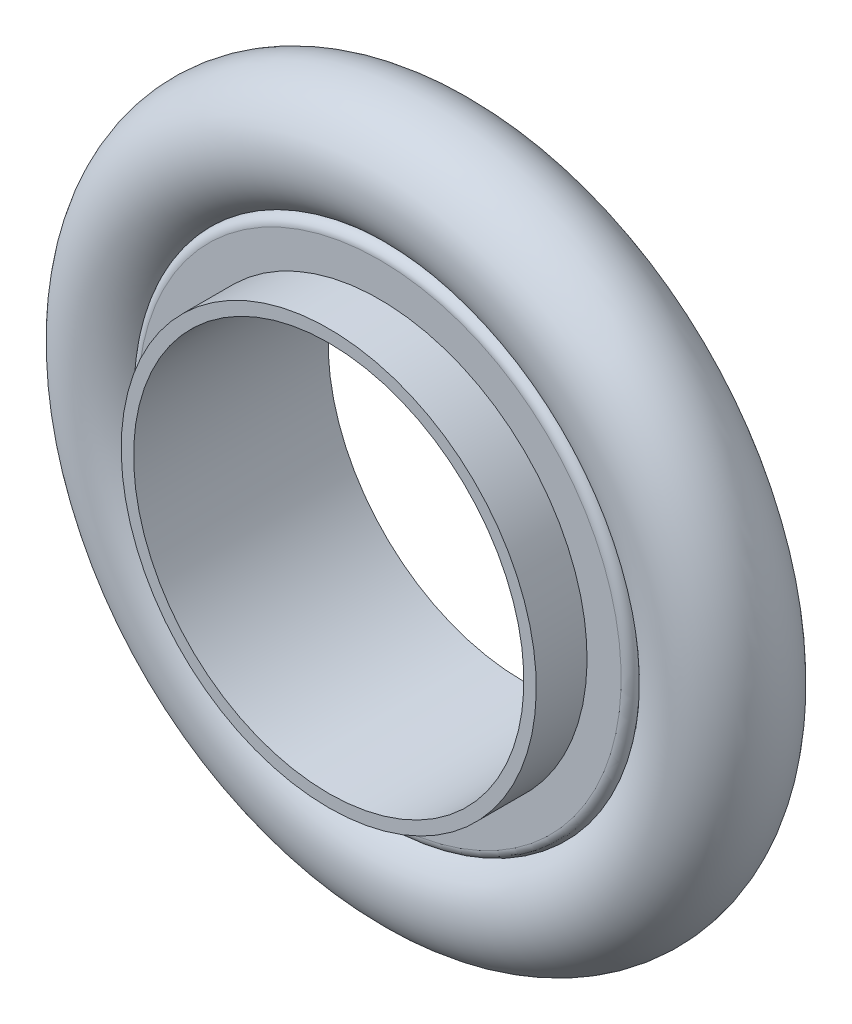
SolidWorks part; units mm, degrees
ref_plane "Front Plane" through (0, 0, 0) normal (0, 0, 1) x (1, 0, 0)
ref_plane "Top Plane" through (0, 0, 0) normal (0, 1, 0) x (1, 0, 0)
ref_plane "Right Plane" through (0, 0, 0) normal (1, 0, 0) x (0, 0, -1)
sketch "Sketch1" plane through (0, 0, 0) normal (1, 0, 0) x (0, 0, -1)
  line L0 (0, 0) -> (0, 12.1613) construction
  line L1 (-3.9878, 0) -> (3.9878, 0) construction
  line L2 (-3.9878, 8.001) -> (3.9878, 8.001) construction
  line L3 (-3.9878, 8.001) -> (-3.9878, 8.509) construction
  line L4 (-3.9878, 8.509) -> (-1.905, 8.509) construction
  line L5 (-1.905, 8.509) -> (-1.905, 9.906) construction
  line L6 (-1.524, 10.287) -> (1.524, 10.287) construction
  line L7 (1.905, 8.509) -> (1.905, 9.906) construction
  line L8 (3.9878, 8.509) -> (1.905, 8.509) construction
  line L9 (3.9878, 8.001) -> (3.9878, 8.509) construction
  line L10 (-3.9878, 14.986) -> (-3.9878, -14.986) construction
  line L11 (3.9878, 8.001) -> (3.9878, -8.001) construction
  line L12 (-3.9878, -9.525) -> (-3.9878, 9.525)
  circle A0 centre (0, 12.1613) radius 2.4157 construction
  arc A1 (-1.905, 9.906) -> (-1.524, 10.287) centre (-1.524, 9.906) cw construction
  arc A2 (1.905, 9.906) -> (1.524, 10.287) centre (1.524, 9.906) ccw construction
  point P7 (0, 0)
  point P10 (0, 8.001)
  point P23 (-3.9878, 0)
  point P26 (3.9878, 0)
  point P31 (-3.9878, 0)
  dimension "D3" = 0.381
  dimension "Ring OD" = 29.1541
  dimension "Length" = 7.9756
  dimension "For Tube OD" = 19.05
  dimension "D2" = 2.286
  dimension "D4" = 3.81
  dimension "For Flange OD" = 29.972
  dimension "Wall Thichness" = 0.508
  dimension "ID" = 16.002
sketch "Sketch4" plane through (0, 0, 0) normal (0, 0, 1) x (1, 0, 0)
  circle A0 centre (0, 0) radius 14.986 construction
  circle A1 centre (0, 0) radius 9.525 construction
sketch "Sketch2" plane through (0, 0, 0) normal (1, 0, 0) x (0, 0, -1)
  line L0 (-1.905, 8.509) -> (-1.905, 9.906) construction
  line L1 (-1.905, 8.509) -> (-1.905, 9.906)
  line L2 (-3.9878, 8.509) -> (-1.905, 8.509) construction
  line L3 (-3.9878, 8.509) -> (-1.905, 8.509)
  line L4 (-3.9878, 8.001) -> (-3.9878, 8.509) construction
  line L5 (-3.9878, 8.001) -> (-3.9878, 8.509)
  line L6 (-3.9878, 8.001) -> (3.9878, 8.001) construction
  line L7 (-3.9878, 8.001) -> (3.9878, 8.001)
  line L8 (3.9878, 8.001) -> (3.9878, 8.509) construction
  line L9 (3.9878, 8.001) -> (3.9878, 8.509)
  line L10 (3.9878, 8.509) -> (1.905, 8.509) construction
  line L11 (3.9878, 8.509) -> (1.905, 8.509)
  line L12 (1.905, 8.509) -> (1.905, 9.906) construction
  line L13 (1.905, 8.509) -> (1.905, 9.906)
  arc A2 (-1.524, 10.287) -> (-1.905, 9.906) centre (-1.524, 9.906) ccw construction
  arc A3 (-1.524, 10.287) -> (-1.905, 9.906) centre (-1.524, 9.906) ccw
  arc A4 (1.905, 9.906) -> (1.524, 10.287) centre (1.524, 9.906) ccw construction
  arc A5 (1.905, 9.906) -> (1.524, 10.287) centre (1.524, 9.906) ccw
  circle A6 centre (0, 12.1613) radius 2.4157 construction
  arc A7 (-1.524, 10.287) -> (1.524, 10.287) centre (0, 12.1613) ccw
revolve "Revolve1" add sketch "Sketch2" angle 360 about L1
sketch "Sketch3" plane through (0, 0, 0) normal (1, 0, 0) x (0, 0, -1)
  circle A0 centre (0, 12.1613) radius 2.4157 construction
  circle A1 centre (0, 12.1613) radius 2.4157
revolve "Revolve2" add sketch "Sketch3" angle 360 about L1
